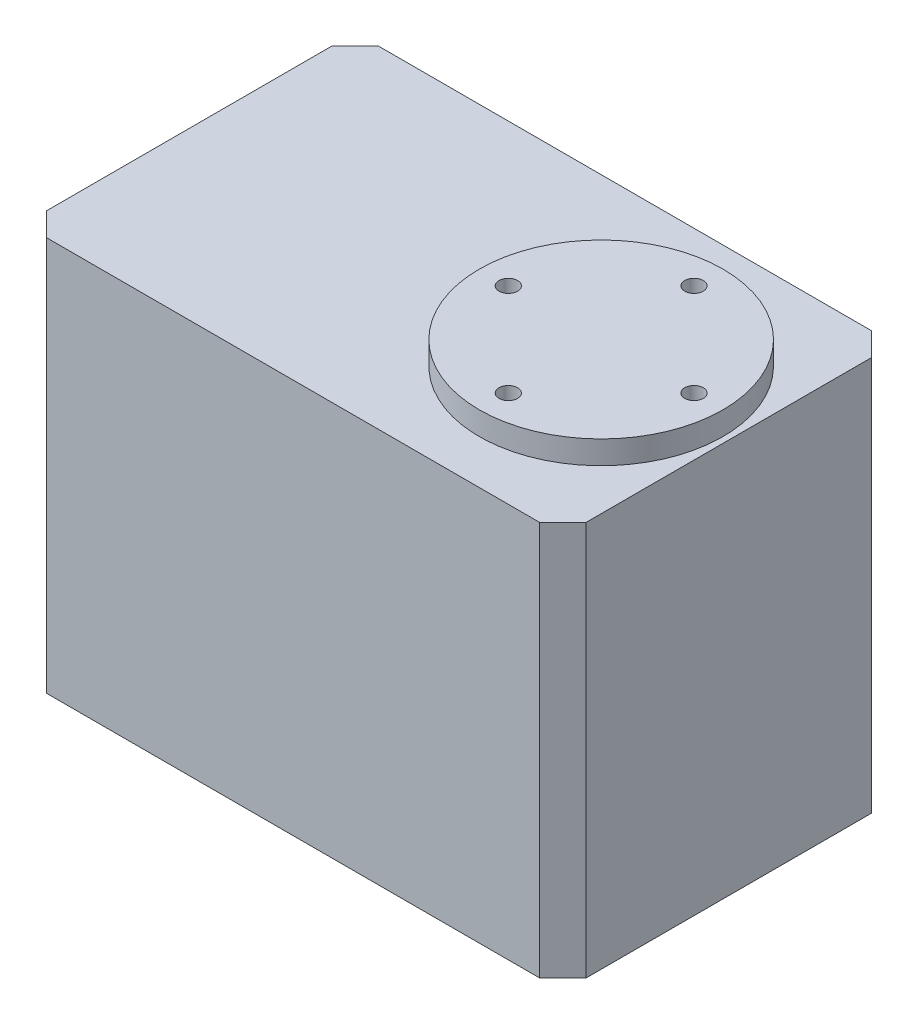
SolidWorks part; units mm, degrees
ref_plane "Plan de face" through (0, 0, 0) normal (0, 0, 1) x (1, 0, 0)
ref_plane "Plan de dessus" through (0, 0, 0) normal (0, 1, 0) x (1, 0, 0)
ref_plane "Plan de droite" through (0, 0, 0) normal (1, 0, 0) x (0, 0, -1)
sketch "Esquisse1" plane through (0, 0, 0) normal (0, 1, 0) x (1, 0, 0)
  line L1 (-23.25, -14.3) -> (23.25, -14.3)
  line L2 (-23.25, -14.3) -> (-23.25, 14.3)
  line L3 (-23.25, 14.3) -> (23.25, 14.3)
  line L4 (23.25, -14.3) -> (23.25, 14.3)
  line L5 (-23.25, -14.3) -> (23.25, 14.3) construction
  line L6 (-23.25, 14.3) -> (23.25, -14.3) construction
  point P0 (0, 0)
  dimension "D1" = 46.5
  dimension "D2" = 28.6
extrude "Boss.-Extru.1" add sketch "Esquisse1" along normal blind 34
chamfer "Chanfrein1" distance 2 angle 45 4 edges at (-23.25, 17, -14.3) (-23.25, 17, 14.3) (23.25, 17, -14.3) (23.25, 17, 14.3)
sketch "Esquisse2" plane through (0, 34, 0) normal (0, 1, 0) x (1, 0, 0)
  line L0 (-19.8, 0) -> (19.8, 0) construction
  line L1 (23.25, -12.3) -> (23.25, 12.3) construction
  circle A0 centre (12.25, 0) radius 10.5
  dimension "D1" = 21
  dimension "D2" = 11
extrude "Boss.-Extru.2" add sketch "Esquisse2" along normal blind 2
sketch "Esquisse3" plane through (0, 36, 0) normal (0, 1, 0) x (1, 0, 0)
  circle A0 centre (12.25, 0) radius 8 construction
  dimension "D1" = 16
hole_wizard "Trou taraudé M2x0.41" positions "Esquisse4" profile "Esquisse5" tap size "M2x0.4" standard "Ansi Metric"
sketch "Esquisse4" plane through (0, 36, 0) normal (0, 1, 0) x (1, 0, 0)
  circle A0 centre (12.25, 0) radius 8 construction
  point P0 (12.25, 8)
  point P4 (20.25, 0)
  point P6 (12.25, -8)
  point P8 (4.25, 0)
cosmetic thread "Filetage de perçage1"
cosmetic thread "Filetage de perçage2"
cosmetic thread "Filetage de perçage3"
cosmetic thread "Filetage de perçage4"
sketch "Esquisse5" plane through (12.25, 36, -8) normal (1, 0, 0) x (0, 0, 1)
  line L0 (0, 0) -> (0, 3.6807)
  line L1 (0, 3.6807) -> (0.8, 3.2)
  line L2 (0.8, 3.2) -> (0.8, 0)
  line L5 (0.8, 0) -> (0, 0)
  line L10 (0, 3.6807) -> (-0.8, 3.2) construction
  line L11 (0, -6.35) -> (0, 107.95) construction
  dimension "Diamètre du trou pour taraudage" = 1.6
  dimension "Profondeur du trou pour taraudage" = 3.2
  dimension "Angle de pointe" = 118
